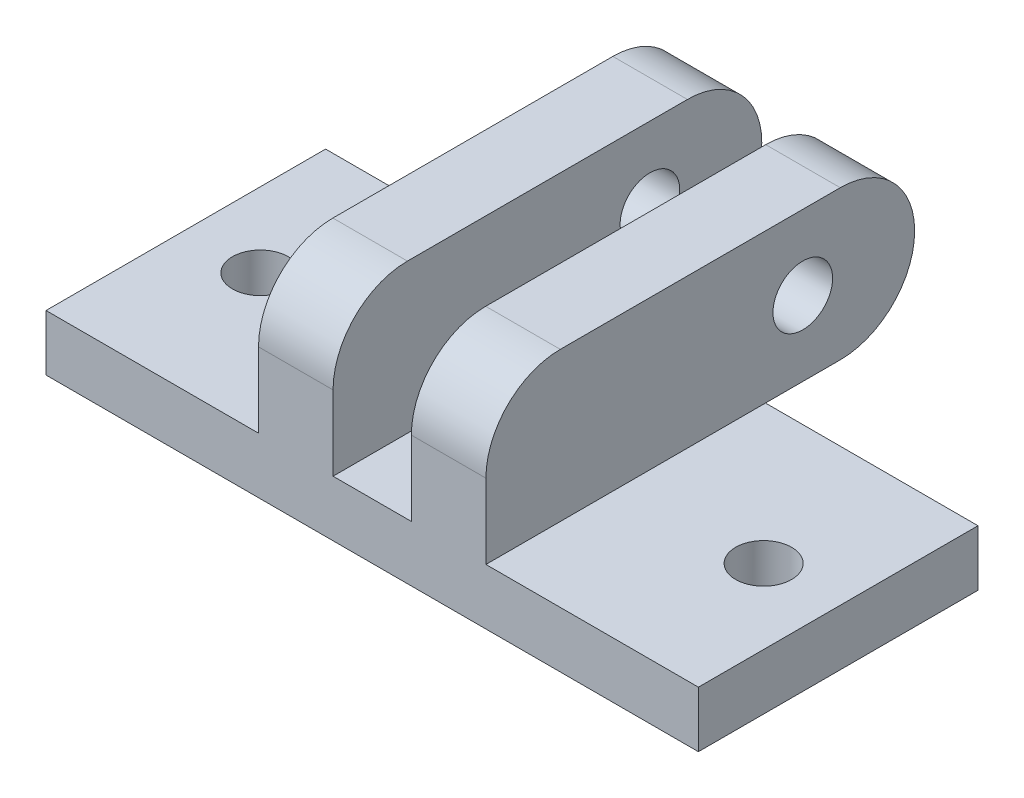
SolidWorks part; units mm, degrees
ref_plane "Front Plane" through (0, 0, 0) normal (0, 0, 1) x (1, 0, 0)
ref_plane "Top Plane" through (0, 0, 0) normal (0, 1, 0) x (1, 0, 0)
ref_plane "Right Plane" through (0, 0, 0) normal (1, 0, 0) x (0, 0, -1)
sketch "Sketch1" plane through (0, 0, 0) normal (0, 1, 0) x (1, 0, 0)
  line L1 (-17.5, -7.5) -> (17.5, -7.5)
  line L2 (-17.5, -7.5) -> (-17.5, 7.5)
  line L3 (-17.5, 7.5) -> (17.5, 7.5)
  line L4 (17.5, -7.5) -> (17.5, 7.5)
  line L5 (-17.5, -7.5) -> (17.5, 7.5) construction
  line L6 (-17.5, 7.5) -> (17.5, -7.5) construction
  point P0 (0, 0)
  dimension "D1" = 15
  dimension "D2" = 35
extrude "Boss-Extrude1" add sketch "Sketch1" along normal blind 3
sketch "Sketch2" plane through (0, 3, 0) normal (0, 1, 0) x (1, 0, 0)
  line L0 (0, 0) -> (0, 18.9835) construction
  line L1 (-17.5, -7.5) -> (17.5, -7.5) construction
  line L2 (-2.1, -7.5) -> (-6.1, -7.5)
  line L3 (-2.1, -7.5) -> (-2.1, 15.5)
  line L4 (-2.1, 15.5) -> (-6.1, 15.5)
  line L5 (-6.1, -7.5) -> (-6.1, 15.5)
  line L6 (2.1, -7.5) -> (6.1, -7.5)
  line L7 (2.1, -7.5) -> (2.1, 15.5)
  line L8 (6.1, -7.5) -> (6.1, 15.5)
  line L9 (2.1, 15.5) -> (6.1, 15.5)
  dimension "D1" = 23
  dimension "D2" = 4
  dimension "D3" = 2.1
extrude "Boss-Extrude2" add sketch "Sketch2" along normal blind 8
sketch "Sketch3" plane through (-6.1, 0, 0) normal (-1, 0, 0) x (0, 0, 1)
  line L0 (-15.5, 6.99) -> (-15.5, 3)
  line L1 (-15.5, 3) -> (-11.51, 3)
  line L3 (-15.5, 7.01) -> (-15.5, 11)
  line L4 (7.5, 11) -> (7.5, 7.01)
  line L6 (-15.5, 11) -> (-11.51, 11)
  line L8 (-15.5, 11) -> (-15.5, 3) construction
  line L10 (7.5, 11) -> (3.51, 11)
  line L11 (-15.5, 11) -> (7.5, 11) construction
  arc A0 (-11.51, 3) -> (-15.5, 6.99) centre (-11.51, 6.99) cw
  arc A1 (-11.51, 11) -> (-15.5, 7.01) centre (-11.51, 7.01) ccw
  arc A2 (7.5, 7.01) -> (3.51, 11) centre (3.51, 7.01) ccw
  circle A3 centre (-9.5, 7) radius 1.6
  point P9 (-15.5, 3)
  point P14 (-15.5, 11)
  point P23 (7.5, 11)
  dimension "D1" = 3.99
  dimension "D2" = 3.99
  dimension "D3" = 3.99
  dimension "D4" = 6
  dimension "D5" = 4
  dimension "D6" = 3.2
extrude "Cut-Extrude1" cut sketch "Sketch3" against normal blind 8
sketch "Sketch5" plane through (6.1, 0, 0) normal (1, 0, 0) x (0, 0, -1)
  line L0 (11.51, 11) -> (15.5, 11)
  line L1 (15.5, 6.99) -> (15.5, 3)
  line L2 (15.5, 11) -> (15.5, 7.01)
  line L3 (15.5, 3) -> (11.51, 3)
  line L4 (-7.5, 7.01) -> (-7.5, 11)
  line L6 (-7.5, 11) -> (-3.51, 11)
  line L8 (15.5, 11) -> (15.5, 3) construction
  arc A0 (11.51, 11) -> (15.5, 7.01) centre (11.51, 7.01) cw
  arc A1 (15.5, 6.99) -> (11.51, 3) centre (11.51, 6.99) cw
  arc A2 (-7.5, 7.01) -> (-3.51, 11) centre (-3.51, 7.01) cw
  circle A3 centre (9.5, 7) radius 1.6
  point P10 (15.5, 11)
  point P21 (-7.5, 11)
  dimension "D1" = 3.99
  dimension "D2" = 3.99
  dimension "D3" = 3.99
  dimension "D6" = 3.2
  dimension "D5" = 6
extrude "Cut-Extrude2" cut sketch "Sketch5" against normal blind 8
sketch "Sketch6" plane through (0, 3, 0) normal (0, 1, 0) x (1, 0, 0)
  line L0 (-6.1, 7.5) -> (-17.5, 7.5) construction
  line L1 (-17.5, 7.5) -> (-17.5, -7.5) construction
  line L2 (17.5, -7.5) -> (17.5, 7.5) construction
  line L3 (17.5, 7.5) -> (6.1, 7.5) construction
  circle A0 centre (13.5, 0) radius 1.5
  circle A1 centre (-13.5, 0) radius 1.5
  dimension "D1" = 3
  dimension "D2" = 3
  dimension "D3" = 7.5
  dimension "D4" = 4
  dimension "D5" = 4
  dimension "D6" = 7.5
  dimension "D7" = 27
extrude "Cut-Extrude3" cut sketch "Sketch6" against normal blind 8
